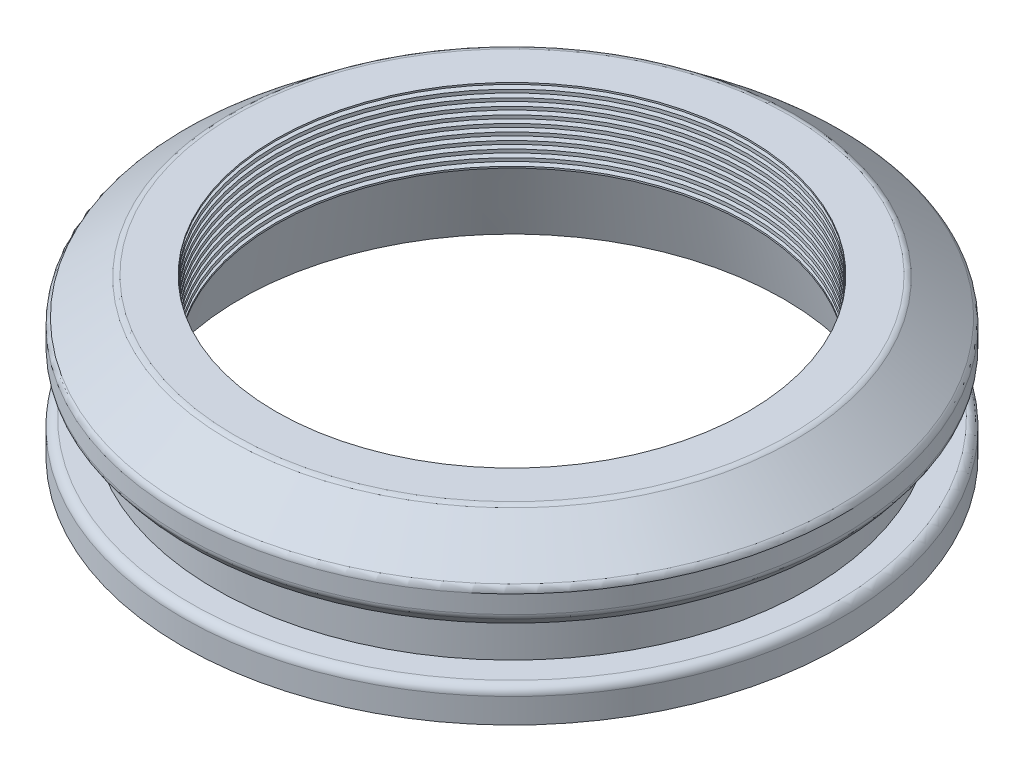
SolidWorks part; units mm, degrees
material "Pure Gold"
ref_plane "Front Plane" through (0, 0, 0) normal (0, 0, 1) x (1, 0, 0)
ref_plane "Top Plane" through (0, 0, 0) normal (0, 1, 0) x (1, 0, 0)
ref_plane "Right Plane" through (0, 0, 0) normal (1, 0, 0) x (0, 0, -1)
sketch "Sketch1" plane through (0, 0, 0) normal (0, 0, 1) x (1, 0, 0)
  line L0 (0, 0) -> (17.78, 0)
  line L1 (23.7188, 25.4) -> (17.78, 0)
  line L2 (28.7988, 25.4) -> (28.7988, 25.908)
  line L3 (28.7988, 25.908) -> (24.4329, 26.29)
  line L4 (24.3789, 26.543) -> (24.201, 26.543) construction
  line L5 (28.7988, 27.178) -> (24.4329, 26.796)
  line L6 (24.4329, 26.29) -> (30.5716, 26.29) construction
  line L7 (25.2071, 26.543) -> (29.9354, 26.543) construction
  line L8 (23.7188, 25.4) -> (28.7988, 25.4)
  line L9 (28.7988, 27.178) -> (28.7988, 28.194)
  line L10 (28.7988, 29.464) -> (24.4329, 29.082)
  line L11 (28.7988, 29.464) -> (28.7988, 30.48)
  line L12 (28.7988, 28.194) -> (24.4329, 28.576)
  line L13 (28.7988, 31.75) -> (24.4329, 31.368)
  line L14 (28.7988, 31.75) -> (28.7988, 32.766)
  line L15 (28.7988, 30.48) -> (24.4329, 30.862)
  line L16 (28.7988, 34.036) -> (24.4329, 33.654)
  line L17 (28.7988, 34.036) -> (28.7988, 35.052)
  line L18 (28.7988, 32.766) -> (24.4329, 33.148)
  line L19 (28.7988, 36.322) -> (24.4329, 35.94)
  line L20 (28.7988, 36.322) -> (28.7988, 37.338)
  line L21 (28.7988, 35.052) -> (24.4329, 35.434)
  line L22 (28.7988, 38.608) -> (24.4329, 38.226)
  line L23 (28.7988, 38.608) -> (28.7988, 39.624)
  line L24 (28.7988, 37.338) -> (24.4329, 37.72)
  line L25 (28.7988, 40.894) -> (24.4329, 40.512)
  line L26 (28.7988, 40.894) -> (28.7988, 41.91)
  line L27 (28.7988, 39.624) -> (24.4329, 40.006)
  line L28 (28.7988, 43.18) -> (24.4329, 42.798)
  line L29 (28.7988, 43.18) -> (28.7988, 44.196)
  line L30 (28.7988, 41.91) -> (24.4329, 42.292)
  line L31 (28.7988, 45.466) -> (24.4329, 45.084)
  line L32 (28.7988, 45.466) -> (28.7988, 46.482)
  line L33 (28.7988, 44.196) -> (24.4329, 44.578)
  line L34 (28.7988, 47.752) -> (24.4329, 47.37)
  line L35 (28.7988, 47.752) -> (28.7988, 48.26)
  line L36 (28.7988, 46.482) -> (24.4329, 46.864)
  line L37 (28.7988, 47.752) -> (28.7988, 48.768) [skipped]
  line L38 (28.7988, 48.26) -> (15.24, 48.26)
  line L39 (15.24, 48.26) -> (0, 36.2406)
  line L40 (0, 36.2406) -> (0, 28.6206)
  line L41 (0, 28.6206) -> (2.54, 25.4)
  line L42 (10.16, 25.4) -> (10.16, 10.16)
  line L43 (10.16, 10.16) -> (0, 10.16)
  line L44 (0, 10.16) -> (0, 0)
  line L45 (2.54, 25.4) -> (10.16, 25.4)
  line L46 (0, 0) -> (203.2, 0) construction
  line L47 (101.6, 0) -> (101.6, 57.1476) construction
  arc A0 (24.4329, 26.796) -> (24.4771, 26.29) centre (24.455, 26.543) ccw
  arc A1 (24.4329, 29.082) -> (24.4771, 28.576) centre (24.455, 28.829) ccw
  arc A2 (24.4329, 31.368) -> (24.4771, 30.862) centre (24.455, 31.115) ccw
  arc A3 (24.4329, 33.654) -> (24.4771, 33.148) centre (24.455, 33.401) ccw
  arc A4 (24.4329, 35.94) -> (24.4771, 35.434) centre (24.455, 35.687) ccw
  arc A5 (24.4329, 38.226) -> (24.4771, 37.72) centre (24.455, 37.973) ccw
  arc A6 (24.4329, 40.512) -> (24.4771, 40.006) centre (24.455, 40.259) ccw
  arc A7 (24.4329, 42.798) -> (24.4771, 42.292) centre (24.455, 42.545) ccw
  arc A8 (24.4329, 45.084) -> (24.4771, 44.578) centre (24.455, 44.831) ccw
  arc A9 (24.4329, 47.37) -> (24.4771, 46.864) centre (24.455, 47.117) ccw
  dimension "D5" = 0.508
  dimension "D8" = 0.254
  dimension "D1" = 5
  dimension "D2" = 5.08
  dimension "D3" = 0.635
  dimension "D4" = 25.4
  dimension "D6" = 5.9388
  dimension "D7" = 17.78
  dimension "D9" = 1.016
  dimension "D11" = 0.508
  dimension "D12" = 10.16
  dimension "D13" = 10.16
  dimension "D14" = 15.24
  dimension "D15" = 7.62
  dimension "D16" = 7.62
  dimension "D17" = 15.24
  dimension "D18" = 203.2
  dimension "D10" = 10
revolve "Revolve1" add sketch "Sketch1" angle 360 about L47
fillet "Fillet1" radius 2.54 1 edges at (101.6, 48.26, -86.36)
fillet "Fillet2" radius 2.54 4 edges at (101.6, 28.6206, -101.6) (101.6, 10.16, -101.6) (101.6, 25.4, -91.44) (101.6, 36.2406, -101.6)
